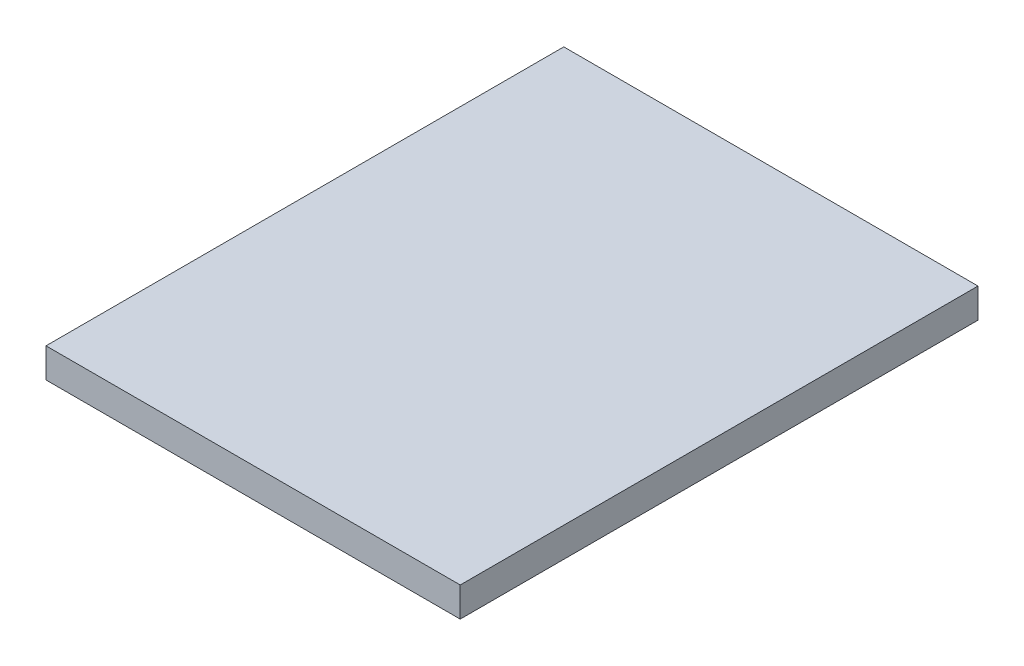
SolidWorks part; units mm, degrees
ref_plane "front" through (0, 0, 0) normal (0, 0, 1) x (1, 0, 0)
ref_plane "top" through (0, 0, 0) normal (0, 1, 0) x (1, 0, 0)
ref_plane "right" through (0, 0, 0) normal (1, 0, 0) x (0, 0, -1)
sketch "Sketch1" plane through (0, 0, 0) normal (0, 1, 0) x (1, 0, 0)
  line L1 (-177.8, 444.5) -> (177.8, 444.5)
  line L2 (-177.8, 444.5) -> (-177.8, 0)
  line L3 (-177.8, 0) -> (177.8, 0)
  line L4 (177.8, 444.5) -> (177.8, 0)
  dimension "D3" = 444.5
  dimension "D2" = 355.6
sketch "Sketch2" plane through (0, 0, 0) normal (0, 1, 0) x (1, 0, 0)
  line L4 (177.8, 444.5) -> (-177.8, 444.5)
  line L5 (-177.8, 444.5) -> (-177.8, 0)
  line L6 (-177.8, 0) -> (177.8, 0)
  line L7 (177.8, 0) -> (177.8, 444.5)
  line L8 (177.8, 444.5) -> (-177.8, 444.5)
  line L9 (-177.8, 444.5) -> (-177.8, 0)
  line L10 (-177.8, 0) -> (177.8, 0)
  line L11 (177.8, 0) -> (177.8, 444.5)
  dimension "D1" = 0
extrude "Extrude2" add sketch "Sketch2" along normal blind 25.4
